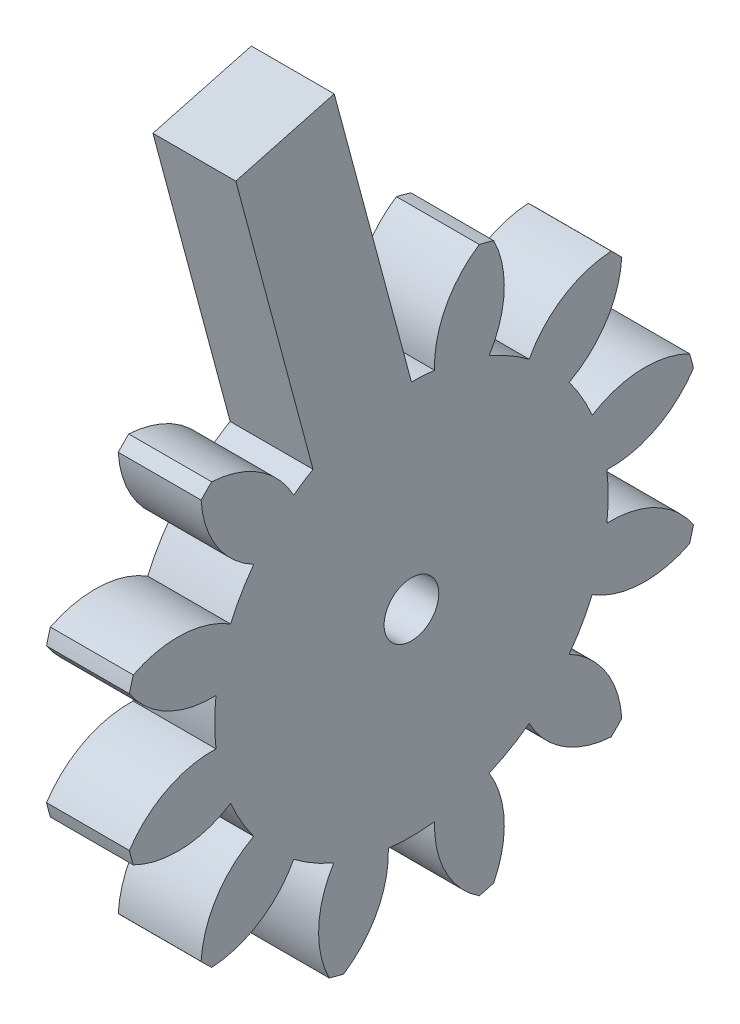
SolidWorks part; units mm, degrees
ref_plane "Plane1" through (0, 0, 0) normal (0, 0, 1) x (1, 0, 0)
ref_plane "Plane2" through (0, 0, 0) normal (0, 1, 0) x (1, 0, 0)
ref_plane "Plane3" through (0, 0, 0) normal (1, 0, 0) x (0, 0, -1)
other "Configuration Table"
sketch "HoldingSke" plane through (0, 0, 0) normal (0, 1, 0) x (1, 0, 0)
  line L0 (0, 0) -> (0.3913, -0.0832)
  line L1 (-15, 0) -> (100, 0) construction
  line L2 (0, 0) -> (-2.1039, 2.3779)
  line L3 (0, 0) -> (-11.863, 4.5341)
  line L4 (0, 0) -> (8.4473, 1.7955)
  line L5 (0, 0) -> (-46.8476, -17.4728)
  line L6 (0, 0) -> (-4.1448, -2.7965)
  line L7 (-2.1039, 2.3779) -> (8.6586, 51.2059)
  line L8 (-76.2, 54.61) -> (-74.8, 54.61)
  line L9 (-71.009, 38.7566) -> (-53.1078, 45.2721)
  line L10 (-76.2, 71.12) -> (104.1128, 71.12)
  line L11 (0, 0) -> (-5, 0)
  line L12 (-76.2, 101.6) -> (-76.113, 101.6)
  line L13 (24.9733, 27.94) -> (52.9518, 28.4284)
  line L14 (24.9733, 27.94) -> (24.9743, 27.94)
  line L15 (24.9733, 27.94) -> (100.4006, 29.5858)
  line L16 (-63.627, -2.5) -> (-12.827, -2.5)
  circle A0 centre (0, 0) radius 4
  circle A1 centre (0, 0) radius 11.874
  circle A2 centre (0, 0) radius 37.5
  circle A3 centre (0, 0) radius 4
  dimension "MHD" = 23.748
  dimension "Hub_dia" = 75
  dimension "Bore" = 8
  dimension "MBD" = 8
  dimension "Num_teeth" = 12
  dimension "Pitch" = 0.4
  dimension "Overall_len" = 50
  dimension "Show_teeth" = 12
  dimension "Thickness" = 5
  dimension "OAL" = 50.0001
  dimension "T_dim" = 1.4
  dimension "Ap" = 20
  dimension "H" = 19.05
  dimension "Pitch_radius" = 180.3128
  dimension "Width" = 5
  dimension "Backlash" = 0.087
  dimension "Addendum_fac" = 1
  dimension "Dedendum_fac" = 1.25
  dimension "Clearance_fac" = 0.25
  dimension "Dedendum_add" = 0.001
  dimension "Module" = 2.5
sketch "BasProSke" plane through (0, 0, 0) normal (0, 1, 0) x (1, 0, 0)
  line L0 (-10, 0) -> (60, 0) construction
  line L1 (0, 0) -> (0, 17.5)
  line L2 (0, 0) -> (5, 0)
  line L3 (5, 0) -> (5, 17.5)
  line L4 (5, 17.5) -> (0, 17.5)
  dimension "Thickness" = 5
  dimension "Diameter" = 35
revolve "Base-Revolve" add sketch "BasProSke" angle 360 about L0
sketch "TooCutSke" plane through (0, 0, 0) normal (1, 0, 0) x (0, 0, -1)
  line L1 (0, 0) -> (0, 107) construction
  line L2 (0, 0) -> (-2.1099, 14.8509) construction
  line L3 (0, 0) -> (-7.7081, 28.7671) construction
  line L4 (-2.1099, 14.8509) -> (-3.8541, 14.3835) construction
  arc A0 (1.3944, 11.7918) -> (-1.3944, 11.7918) centre (0, 0) ccw
  arc A1 (4.1219, 17.0338) -> (-4.1219, 17.0338) centre (0, 0) ccw
  circle A2 centre (0, 0) radius 15 construction
  circle A3 centre (0, 0) radius 14.0954 construction
  arc A4 (-1.3944, 11.7918) -> (-4.1219, 17.0338) centre (-7.3907, 12.0024) ccw
  arc A5 (4.1219, 17.0338) -> (1.3944, 11.7918) centre (7.3907, 12.0024) ccw
  dimension "Root_dia" = 23.748
  dimension "Overcut_dia" = 35.0508
  dimension "Pitch_dia" = 30
  dimension "Base_dia" = 28.1908
  dimension "Flank_rad" = 6
  dimension "Half_ang" = 15
  dimension "Half_CT" = 1.8056
extrude "ToothCut" cut sketch "TooCutSke" along normal through all
fillet "Breaks" [suppressed] radius 0.05
fillet "RootFillets" [suppressed] radius 0.626
pattern_circular "TeethCuts" count 12 every 30 about axis through (-10, 0, 0) along (1, 0, 0) of "ToothCut", "RootFillets", "Breaks"
sketch "HubNeaOneSke" plane through (0, 0, 0) normal (-1, 0, 0) x (0, 0, 1)
  circle A0 centre (0, 0) radius 11.874
  dimension "Diameter" = 23.748
extrude "HubNearOne" [suppressed] add sketch "HubNeaOneSke" along normal blind 45.0001
sketch "HubNeaBotSke" plane through (0, 0, 0) normal (-1, 0, 0) x (0, 0, 1)
  circle A0 centre (0, 0) radius 11.874
  dimension "Diameter" = 23.748
extrude "HubNearBoth" [suppressed] add sketch "HubNeaBotSke" along normal blind 22.5
ref_plane "FarPln" through (5, 0, 0) normal (1, 0, 0) x (0, 0, -1)
sketch "HubFarSke" plane through (5, 0, 0) normal (1, 0, 0) x (0, 0, -1)
  circle A0 centre (0, 0) radius 11.874
  dimension "Diameter" = 23.748
extrude "HubFar" [suppressed] add sketch "HubFarSke" along normal blind 22.5
sketch "BorSke" plane through (0, 0, 0) normal (1, 0, 0) x (0, 0, -1)
  circle A0 centre (0, 0) radius 4
  dimension "Diameter" = 8
extrude "Bore" cut sketch "BorSke" along normal mid plane 100.0001
sketch "KeySke" plane through (0, 0, 0) normal (1, 0, 0) x (0, 0, -1)
  line L0 (-1.5, 0) -> (-1.5, 5.4)
  line L1 (-1.5, 5.4) -> (1.5, 5.4)
  line L2 (1.5, 5.4) -> (1.5, 0)
  line L3 (0, 0) -> (0, 34) construction
  line L4 (-1.5, 0) -> (1.5, 0)
  dimension "Offset" = 5.4
  dimension "Width" = 3
extrude "Keyway" [suppressed] cut sketch "KeySke" along normal mid plane 100.0001
pattern_circular "Keyway2" [suppressed] count 2 every 90 about axis through (-10, 0, 0) along (1, 0, 0)
sketch "草图1" plane through (5, 0, 0) normal (1, 0, 0) x (0, 0, -1)
  circle A0 centre (0, 0) radius 14.0954
  arc A49 (-12.6888, 12.0517) -> (-9.5148, 7.1035) centre (-6.699, 12.4017) ccw
  arc A50 (-9.5148, 7.1035) -> (-10.9092, 4.6884) centre (0, 0) ccw
  arc A51 (-10.9092, 4.6884) -> (-16.7815, 4.963) centre (-14.0897, -0.3993) ccw
  arc A52 (-16.7815, 4.963) -> (-17.0147, 4.0927) centre (0, 0) ccw
  arc A53 (-17.0147, 4.0927) -> (-11.7918, 1.3944) centre (-12.0024, 7.3907) ccw
  arc A54 (-11.7918, 1.3944) -> (-11.7918, -1.3944) centre (0, 0) ccw
  arc A55 (-11.7918, -1.3944) -> (-17.0147, -4.0927) centre (-12.0024, -7.3907) ccw
  arc A56 (-17.0147, -4.0927) -> (-16.7815, -4.963) centre (0, 0) ccw
  arc A57 (-16.7815, -4.963) -> (-10.9092, -4.6884) centre (-14.0897, 0.3993) ccw
  arc A58 (-10.9092, -4.6884) -> (-9.5148, -7.1035) centre (0, 0) ccw
  arc A59 (-9.5148, -7.1035) -> (-12.6888, -12.0517) centre (-6.699, -12.4017) ccw
  arc A60 (-12.6888, -12.0517) -> (-12.0517, -12.6888) centre (0, 0) ccw
  arc A61 (-12.0517, -12.6888) -> (-7.1035, -9.5148) centre (-12.4017, -6.699) ccw
  arc A62 (-7.1035, -9.5148) -> (-4.6884, -10.9092) centre (0, 0) ccw
  arc A63 (-4.6884, -10.9092) -> (-4.963, -16.7815) centre (0.3993, -14.0897) ccw
  arc A64 (-4.963, -16.7815) -> (-4.0927, -17.0147) centre (0, 0) ccw
  arc A65 (-4.0927, -17.0147) -> (-1.3944, -11.7918) centre (-7.3907, -12.0024) ccw
  arc A66 (-1.3944, -11.7918) -> (1.3944, -11.7918) centre (0, 0) ccw
  arc A67 (1.3944, -11.7918) -> (4.0927, -17.0147) centre (7.3907, -12.0024) ccw
  arc A68 (4.0927, -17.0147) -> (4.963, -16.7815) centre (0, 0) ccw
  arc A69 (4.963, -16.7815) -> (4.6884, -10.9092) centre (-0.3993, -14.0897) ccw
  arc A70 (4.6884, -10.9092) -> (7.1035, -9.5148) centre (0, 0) ccw
  arc A71 (7.1035, -9.5148) -> (12.0517, -12.6888) centre (12.4017, -6.699) ccw
  arc A72 (12.0517, -12.6888) -> (12.6888, -12.0517) centre (0, 0) ccw
  arc A73 (12.6888, -12.0517) -> (9.5148, -7.1035) centre (6.699, -12.4017) ccw
  arc A74 (9.5148, -7.1035) -> (10.9092, -4.6884) centre (0, 0) ccw
  arc A75 (10.9092, -4.6884) -> (16.7815, -4.963) centre (14.0897, 0.3993) ccw
  arc A76 (16.7815, -4.963) -> (17.0147, -4.0927) centre (0, 0) ccw
  arc A77 (17.0147, -4.0927) -> (11.7918, -1.3944) centre (12.0024, -7.3907) ccw
  arc A78 (11.7918, -1.3944) -> (11.7918, 1.3944) centre (0, 0) ccw
  arc A79 (11.7918, 1.3944) -> (17.0147, 4.0927) centre (12.0024, 7.3907) ccw
  arc A80 (17.0147, 4.0927) -> (16.7815, 4.963) centre (0, 0) ccw
  arc A81 (16.7815, 4.963) -> (10.9092, 4.6884) centre (14.0897, -0.3993) ccw
  arc A82 (10.9092, 4.6884) -> (9.5148, 7.1035) centre (0, 0) ccw
  arc A83 (9.5148, 7.1035) -> (12.6888, 12.0517) centre (6.699, 12.4017) ccw
  arc A84 (12.6888, 12.0517) -> (12.0517, 12.6888) centre (0, 0) ccw
  arc A85 (12.0517, 12.6888) -> (7.1035, 9.5148) centre (12.4017, 6.699) ccw
  arc A86 (7.1035, 9.5148) -> (4.6884, 10.9092) centre (0, 0) ccw
  arc A87 (4.6884, 10.9092) -> (4.963, 16.7815) centre (-0.3993, 14.0897) ccw
  arc A88 (4.963, 16.7815) -> (4.0927, 17.0147) centre (0, 0) ccw
  arc A89 (4.0927, 17.0147) -> (1.3944, 11.7918) centre (7.3907, 12.0024) ccw
  arc A90 (1.3944, 11.7918) -> (-1.3944, 11.7918) centre (0, 0) ccw
  arc A91 (-1.3944, 11.7918) -> (-4.0927, 17.0147) centre (-7.3907, 12.0024) ccw
  arc A92 (-4.0927, 17.0147) -> (-4.963, 16.7815) centre (0, 0) ccw
  arc A93 (-4.963, 16.7815) -> (-4.6884, 10.9092) centre (0.3993, 14.0897) ccw
  arc A94 (-4.6884, 10.9092) -> (-7.1035, 9.5148) centre (0, 0) ccw
  arc A95 (-7.1035, 9.5148) -> (-12.0517, 12.6888) centre (-12.4017, 6.699) ccw
  arc A96 (-12.0517, 12.6888) -> (-12.6888, 12.0517) centre (0, 0) ccw
  arc A97 (-12.6888, 12.0517) -> (-9.5148, 7.1035) centre (-6.699, 12.4017) ccw
  arc A98 (-9.5148, 7.1035) -> (-10.9092, 4.6884) centre (0, 0) ccw
  arc A99 (-10.9092, 4.6884) -> (-16.7815, 4.963) centre (-14.0897, -0.3993) ccw
  arc A100 (-16.7815, 4.963) -> (-17.0147, 4.0927) centre (0, 0) ccw
  arc A101 (-17.0147, 4.0927) -> (-11.7918, 1.3944) centre (-12.0024, 7.3907) ccw
  arc A102 (-11.7918, 1.3944) -> (-11.7918, -1.3944) centre (0, 0) ccw
  arc A103 (-11.7918, -1.3944) -> (-17.0147, -4.0927) centre (-12.0024, -7.3907) ccw
  arc A104 (-17.0147, -4.0927) -> (-16.7815, -4.963) centre (0, 0) ccw
  arc A105 (-16.7815, -4.963) -> (-10.9092, -4.6884) centre (-14.0897, 0.3993) ccw
  arc A106 (-10.9092, -4.6884) -> (-9.5148, -7.1035) centre (0, 0) ccw
  arc A107 (-9.5148, -7.1035) -> (-12.6888, -12.0517) centre (-6.699, -12.4017) ccw
  arc A108 (-12.6888, -12.0517) -> (-12.0517, -12.6888) centre (0, 0) ccw
  arc A109 (-12.0517, -12.6888) -> (-7.1035, -9.5148) centre (-12.4017, -6.699) ccw
  arc A110 (-7.1035, -9.5148) -> (-4.6884, -10.9092) centre (0, 0) ccw
  arc A111 (-4.6884, -10.9092) -> (-4.963, -16.7815) centre (0.3993, -14.0897) ccw
  arc A112 (-4.963, -16.7815) -> (-4.0927, -17.0147) centre (0, 0) ccw
  arc A113 (-4.0927, -17.0147) -> (-1.3944, -11.7918) centre (-7.3907, -12.0024) ccw
  arc A114 (-1.3944, -11.7918) -> (1.3944, -11.7918) centre (0, 0) ccw
  arc A115 (1.3944, -11.7918) -> (4.0927, -17.0147) centre (7.3907, -12.0024) ccw
  arc A116 (4.0927, -17.0147) -> (4.963, -16.7815) centre (0, 0) ccw
  arc A117 (4.963, -16.7815) -> (4.6884, -10.9092) centre (-0.3993, -14.0897) ccw
  arc A118 (4.6884, -10.9092) -> (7.1035, -9.5148) centre (0, 0) ccw
  arc A119 (7.1035, -9.5148) -> (12.0517, -12.6888) centre (12.4017, -6.699) ccw
  arc A120 (12.0517, -12.6888) -> (12.6888, -12.0517) centre (0, 0) ccw
  arc A121 (12.6888, -12.0517) -> (9.5148, -7.1035) centre (6.699, -12.4017) ccw
  arc A122 (9.5148, -7.1035) -> (10.9092, -4.6884) centre (0, 0) ccw
  arc A123 (10.9092, -4.6884) -> (16.7815, -4.963) centre (14.0897, 0.3993) ccw
  arc A124 (16.7815, -4.963) -> (17.0147, -4.0927) centre (0, 0) ccw
  arc A125 (17.0147, -4.0927) -> (11.7918, -1.3944) centre (12.0024, -7.3907) ccw
  arc A126 (11.7918, -1.3944) -> (11.7918, 1.3944) centre (0, 0) ccw
  arc A127 (11.7918, 1.3944) -> (17.0147, 4.0927) centre (12.0024, 7.3907) ccw
  arc A128 (17.0147, 4.0927) -> (16.7815, 4.963) centre (0, 0) ccw
  arc A129 (16.7815, 4.963) -> (10.9092, 4.6884) centre (14.0897, -0.3993) ccw
  arc A130 (10.9092, 4.6884) -> (9.5148, 7.1035) centre (0, 0) ccw
  arc A131 (9.5148, 7.1035) -> (12.6888, 12.0517) centre (6.699, 12.4017) ccw
  arc A132 (12.6888, 12.0517) -> (12.0517, 12.6888) centre (0, 0) ccw
  arc A133 (12.0517, 12.6888) -> (7.1035, 9.5148) centre (12.4017, 6.699) ccw
  arc A134 (7.1035, 9.5148) -> (4.6884, 10.9092) centre (0, 0) ccw
  arc A135 (4.6884, 10.9092) -> (4.963, 16.7815) centre (-0.3993, 14.0897) ccw
  arc A136 (4.963, 16.7815) -> (4.0927, 17.0147) centre (0, 0) ccw
  arc A137 (4.0927, 17.0147) -> (1.3944, 11.7918) centre (7.3907, 12.0024) ccw
  arc A138 (1.3944, 11.7918) -> (-1.3944, 11.7918) centre (0, 0) ccw
  arc A139 (-1.3944, 11.7918) -> (-4.0927, 17.0147) centre (-7.3907, 12.0024) ccw
  arc A140 (-4.0927, 17.0147) -> (-4.963, 16.7815) centre (0, 0) ccw
  arc A141 (-4.963, 16.7815) -> (-4.6884, 10.9092) centre (0.3993, 14.0897) ccw
  arc A142 (-4.6884, 10.9092) -> (-7.1035, 9.5148) centre (0, 0) ccw
  arc A143 (-7.1035, 9.5148) -> (-12.0517, 12.6888) centre (-12.4017, 6.699) ccw
  arc A144 (-12.0517, 12.6888) -> (-12.6888, 12.0517) centre (0, 0) ccw
  dimension "D1" = 28.1908
  dimension "D2" = 0
sketch "草图2" plane through (5, 0, 0) normal (1, 0, 0) x (0, 0, -1)
  line L0 (0, 11.874) -> (-5.937, 10.2832)
  line L1 (-5.937, 10.2832) -> (-10.5957, 27.6699)
  line L2 (-10.5957, 27.6699) -> (-4.6587, 29.2607)
  line L3 (-4.6587, 29.2607) -> (0, 11.874)
  arc A0 (-4.6884, 10.9092) -> (-7.1035, 9.5148) centre (0, 0) ccw construction
  arc A2 (1.3944, 11.7918) -> (-1.3944, 11.7918) centre (0, 0) ccw construction
  point P17 (-5.937, 10.2832)
  point P21 (0, 11.874)
extrude "凸台-拉伸1" add sketch "草图2" against normal blind 5
sketch "草图3" plane through (5, 0, 0) normal (1, 0, 0) x (0, 0, -1)
  circle A0 centre (0, 0) radius 5.7875
  circle A1 centre (0, 0) radius 1.65
  dimension "D1" = 3.3
extrude "凸台-拉伸2" add sketch "草图3" against normal blind 5
equation "' \"Module@HoldingSke\" = 6.35"
equation "' \"Num_teeth@HoldingSke\" = 12"
equation "' \"Ap@HoldingSke\" =  20"
equation "' \"Ap@HoldingSke\" = 20"
equation "' \"Width@HoldingSke\" = 0.5 * 25.4"
equation "' \"Hub_dia@HoldingSke\"= 1 * 25.4"
equation "' \"Hub_dia@HoldingSke\" = 1 * 25.4"
equation "' \"Overall_len@HoldingSke\" = 1.0 * 25.4"
equation "' \"Bore@HoldingSke\" = 0.75 * 25.4"
equation "' \"T_dim@HoldingSke\" = 0.1 * 25.4"
equation "' \"Width@KeySke\" = 0.25 * 25.4"
equation "' \"Show_teeth@HoldingSke\" = 13"
equation "' \"Backlash@HoldingSke\" = 0.009 * 25.4"
equation "' \"Addendum_fac@HoldingSke\" = 1.0"
equation "' \"Dedendum_fac@HoldingSke\" = 1.25"
equation "' \"Dedendum_add@HoldingSke\" = 0.00005 * 25.4"
equation "' \"Clearance_fac@HoldingSke\" = 0.25"
equation "\"Pitch@HoldingSke\" = 1 / \"Module@HoldingSke\""
equation "\"Overcut_dia@TooCutSke\" = (\"Num_teeth@HoldingSke\" + 2 * \"Addendum_fac@HoldingSke\") / \"Pitch@HoldingSke\" + 0.002 * 25.4"
equation "\"Pitch_dia@TooCutSke\" = \"Num_teeth@HoldingSke\" / \"Pitch@HoldingSke\""
equation "\"Base_dia@TooCutSke\" = \"Num_teeth@HoldingSke\" / \"Pitch@HoldingSke\" * cos((\"Ap@HoldingSke\"  * 3.14159265 / 180))"
equation "\"Root_dia@TooCutSke\" = (\"Num_teeth@HoldingSke\" + 2) / \"Pitch@HoldingSke\" - 2 * (\"Addendum_fac@HoldingSke\" + \"Dedendum_fac@HoldingSke\") / \"Pitch@HoldingSke\" - \"Dedendum_add@HoldingSke\" * 2"
equation "\"Half_ang@TooCutSke\" = 180 / \"Num_teeth@HoldingSke\""
equation "\"Half_CT@TooCutSke\" = \"Num_teeth@HoldingSke\" / \"Pitch@HoldingSke\" * sin((3.14159265 / 2 / \"Num_teeth@HoldingSke\")) / 2 - 7 * \"Backlash@HoldingSke\" / 4"
equation "\"Flank_rad@TooCutSke\" = \"Num_teeth@HoldingSke\" / \"Pitch@HoldingSke\" / 5"
equation "\"Radius@RootFillets\" = \"Clearance_fac@HoldingSke\" / \"Pitch@HoldingSke\" + \"Dedendum_add@HoldingSke\""
equation "\"Break_rad@Breaks\" = 0.02 / \"Pitch@HoldingSke\""
equation "\"Thickness@HoldingSke\" = \"Width@HoldingSke\""
equation "\"OAL@HoldingSke\" = \"Thickness@HoldingSke\""
equation "\"MHD@HoldingSke\" = (\"Num_teeth@HoldingSke\" + 2) / \"Pitch@HoldingSke\" - 2 * (\"Addendum_fac@HoldingSke\" + \"Dedendum_fac@HoldingSke\")  / \"Pitch@HoldingSke\" - \"Dedendum_add@HoldingSke\" * 2"
equation "\"MBD@HoldingSke\" = (\"Num_teeth@HoldingSke\" + 2) / \"Pitch@HoldingSke\" - 2 * (\"Addendum_fac@HoldingSke\" + \"Dedendum_fac@HoldingSke\")  / \"Pitch@HoldingSke\" - \"Dedendum_add@HoldingSke\" * 2 - 0.002 * 25.4"
equation "\"MHD@HoldingSke\" = ((sgn( \"MHD@HoldingSke\" - \"Hub_dia@HoldingSke\" )-1)*( \"MHD@HoldingSke\" - \"Hub_dia@HoldingSke\" ))/-2+ \"Hub_dia@HoldingSke\""
equation "\"MBD@HoldingSke\" = ((sgn( \"MBD@HoldingSke\" - \"Bore@HoldingSke\" )-1)*( \"MBD@HoldingSke\" - \"Bore@HoldingSke\" ))/-2+ \"Bore@HoldingSke\""
equation "\"OAL@HoldingSke\" = ((sgn( \"OAL@HoldingSke\" - \"Overall_len@HoldingSke\" )+1)*( \"OAL@HoldingSke\" - \"Overall_len@HoldingSke\" ))/2 + \"Overall_len@HoldingSke\" + 0.000002 * 25.4"
equation "\"Num_teeth@TeethCuts\" = int( \"Show_teeth@HoldingSke\" ) + 1"
equation "\"Num_teeth@TeethCuts\" = ((sgn( \"Num_teeth@TeethCuts\" - \"Num_teeth@HoldingSke\" )-1)*( \"Num_teeth@TeethCuts\" - \"Num_teeth@HoldingSke\" ))/-2+ \"Num_teeth@HoldingSke\""
equation "\"Num_teeth@TeethCuts\" = ((sgn( \"Num_teeth@TeethCuts\" - 2.0)+1)*( \"Num_teeth@TeethCuts\" - 2.0))/2 +2.0"
equation "\"Angle@TeethCuts\" = 360.0 / \"Num_teeth@HoldingSke\""
equation "\"Diameter@BasProSke\" = (\"Num_teeth@HoldingSke\" + 2 * \"Addendum_fac@HoldingSke\") / \"Pitch@HoldingSke\""
equation "\"Thickness@BasProSke\"  = \"Thickness@HoldingSke\""
equation "' \"Fillet_rad@BasProSke\" =  \"Thickness@HoldingSke\" * 0.05"
equation "' \"Fillet_rad@BasProSke\" = \"Thickness@HoldingSke\" * 0.05"
equation "\"MHD@HoldingSke\" = ((sgn( \"MHD@HoldingSke\" - \"Root_dia@TooCutSke\" )-1)*( \"MHD@HoldingSke\" - \"Root_dia@TooCutSke\" ))/-2+ \"Root_dia@TooCutSke\""
equation "\"Diameter@HubNeaOneSke\" = \"MHD@HoldingSke\""
equation "\"Length@HubNearOne\" = \"OAL@HoldingSke\" - \"Thickness@BasProSke\""
equation "\"Diameter@HubNeaBotSke\" = \"MHD@HoldingSke\""
equation "\"Length@HubNearBoth\" = ( \"OAL@HoldingSke\" - \"Thickness@BasProSke\" ) / 2.0"
equation "\"Thickness@FarPln\" = \"Thickness@BasProSke\""
equation "\"Diameter@HubFarSke\" = \"MHD@HoldingSke\""
equation "\"Length@HubFar\" = ( \"OAL@HoldingSke\" - \"Thickness@BasProSke\" ) / 2.0"
equation "\"Diameter@BorSke\" = \"MBD@HoldingSke\""
equation "\"D1@Bore\" = \"OAL@HoldingSke\" * 2.0"
equation "\"D1@Keyway\" = \"OAL@HoldingSke\" * 2.0"
equation "\"Offset@KeySke\" = \"T_dim@HoldingSke\" + \"MBD@HoldingSke\" / 2.0"
